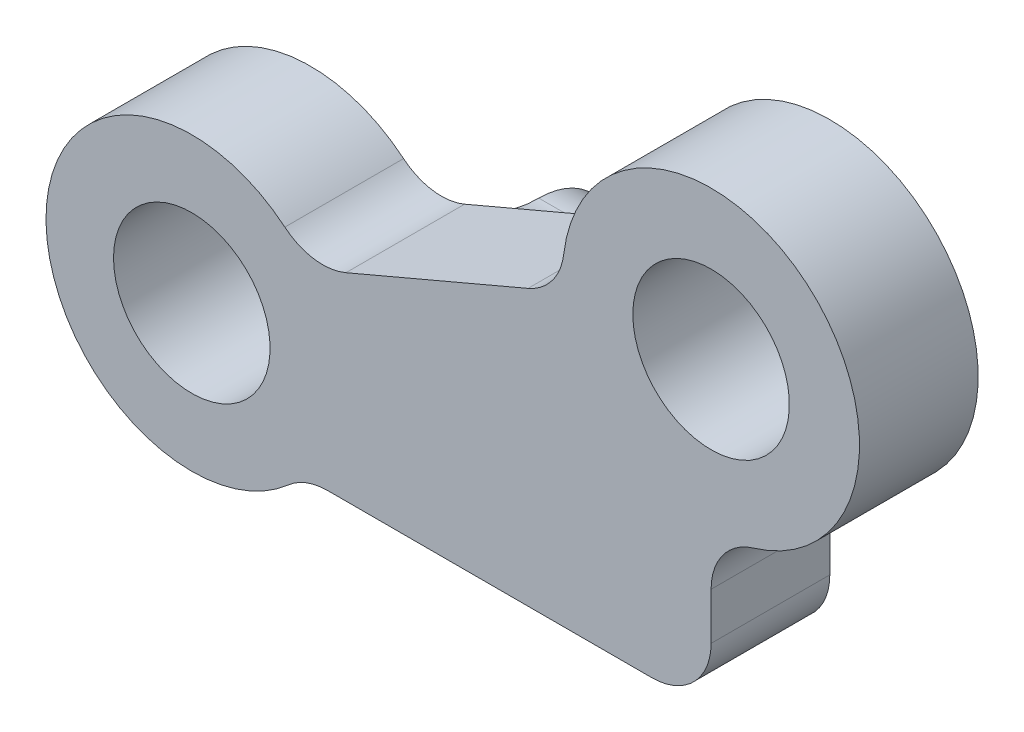
SolidWorks part; units mm, degrees
ref_plane "Front Plane" through (0, 0, 0) normal (0, 0, 1) x (1, 0, 0)
ref_plane "Top Plane" through (0, 0, 0) normal (0, 1, 0) x (1, 0, 0)
ref_plane "Right Plane" through (0, 0, 0) normal (1, 0, 0) x (0, 0, -1)
ref_plane "Plane3" through (0, 0, 0) normal (0, 0, -1) x (-1, 0, 0)
sketch "Sketch17" plane through (0, 0, 0) normal (0, 0, -1) x (-1, 0, 0)
  line L0 (-43.2731, 29.4209) -> (-51.8645, 33.076)
  line L1 (-56.8391, 28.5799) -> (-56.8391, 23.2923)
  line L2 (-56.8391, 23.2923) -> (-43.0826, 23.2923)
  arc A0 (-43.0826, 23.2923) -> (-43.2731, 29.4209) centre (-39.3406, 26.4759) ccw
  arc A1 (-51.8645, 33.076) -> (-56.8391, 28.5799) centre (-56.8391, 33.5799) ccw
extrude "Boss-Extrude3" add sketch "Sketch17" against normal blind 4
hole_wizard "Hole3" positions "Sketch19" profile "Sketch18" legacy
sketch "Sketch19" plane through (0, 0, 0) normal (0, 0, -1) x (-1, 0, 0)
  point P0 (-39.3406, 26.4759)
  point P1 (-56.8391, 33.5799)
sketch "Sketch18" plane through (39.3406, 26.4759, 0) normal (1, 0, 0) x (0, 1, 0)
  line L0 (0, 0) -> (0, 4)
  line L1 (0, 4) -> (2.6375, 4)
  line L2 (2.6375, 4) -> (2.6375, 0)
  line L3 (2.6375, 0) -> (0, 0)
  line L4 (0, 110) -> (0, -10) construction
  dimension "Diameter" = 5.275
  dimension "Depth" = 4
fillet "Fillet3" radius 2 5 edges at (51.8645, 33.076, 2) (43.0826, 23.2923, 2) (43.2731, 29.4209, 2) (56.8391, 23.2923, 2) (56.8391, 28.5799, 2)
ref_plane "Plane4" through (45, 0, 0) normal (1, 0, 0) x (0, 0, -1)
ref_plane "Plane5" through (47, 0, 0) normal (1, 0, 0) x (0, 0, -1)
sketch "Sketch25" plane through (47, 0, 0) normal (1, 0, 0) x (0, 0, -1)
  line L0 (0, 23.2923) -> (0, 30.1441)
  line L1 (0, 28.7883) -> (0, 38.5799) construction
  circle A0 centre (2.034, 26.8496) radius 1.5065
  arc A1 (2.034, 24.3496) -> (2.034, 29.3496) centre (2.034, 26.8496) ccw
  spline S0 degree 2 poles (2.034, 29.3496) (0.8443, 29.3488) (0, 30.1441) knots 0 0 0 1 1 1
  spline S1 degree 2 poles (2.034, 24.3496) (0.7258, 24.3594) (0, 23.2923) knots 0 0 0 1 1 1
  point P9 (0.8095, 24.0566)
  point P10 (0, 0)
  point P11 (0, 30.1441)
extrude "Boss-Extrude4" add sketch "Sketch25" against normal up to surface (2 mm away) up to plane "Plane4"
